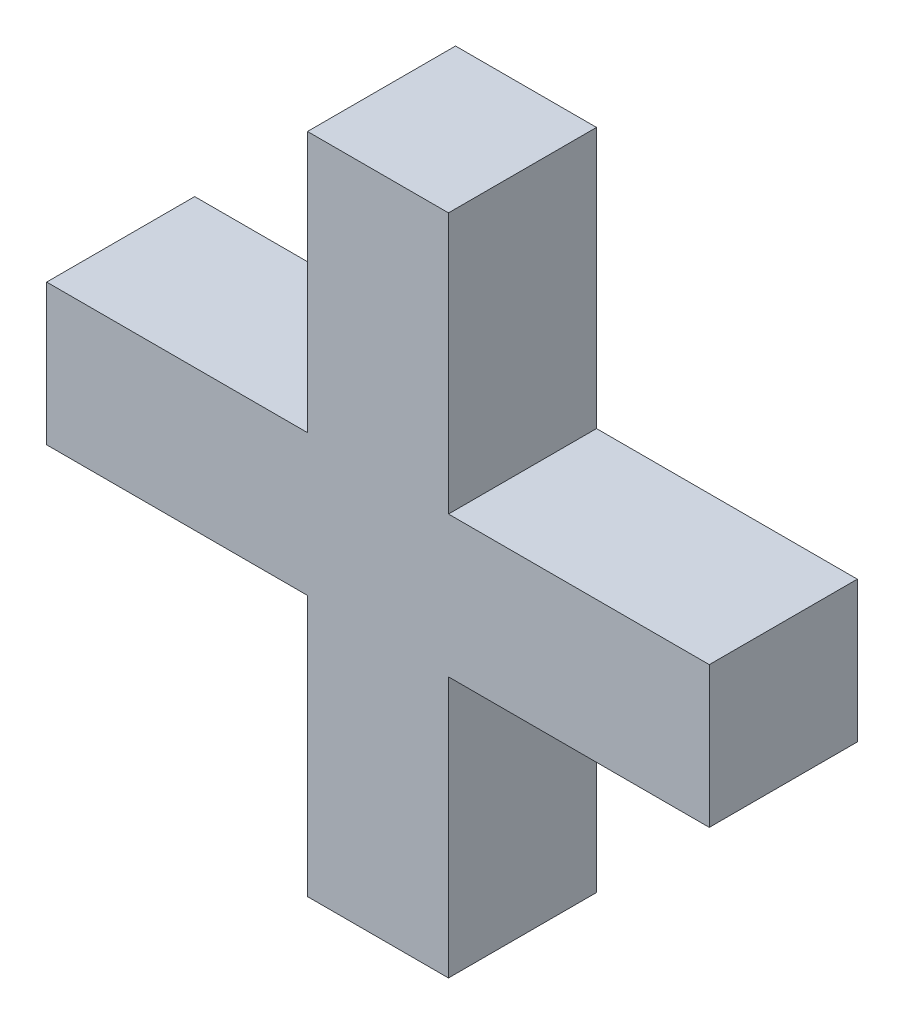
SolidWorks part; units mm, degrees
ref_plane "Спереди" through (0, 0, 0) normal (0, 0, 1) x (1, 0, 0)
ref_plane "Сверху" through (0, 0, 0) normal (0, 1, 0) x (1, 0, 0)
ref_plane "Справа" through (0, 0, 0) normal (1, 0, 0) x (0, 0, -1)
sketch "Эскиз1" plane through (0, 0, 0) normal (0, 0, 1) x (1, 0, 0)
  line L0 (0, 28.5) -> (0, 47)
  line L5 (0, 0) -> (10, 0)
  line L6 (0, 0) -> (0, 18.5)
  line L7 (0, 47) -> (10, 47)
  line L8 (10, 0) -> (10, 18.5)
  line L9 (-18.5, 28.5) -> (0, 28.5)
  line L10 (-18.5, 28.5) -> (-18.5, 18.5)
  line L11 (-18.5, 18.5) -> (0, 18.5)
  line L12 (28.5, 28.5) -> (28.5, 18.5)
  line L13 (10, 28.5) -> (28.5, 28.5)
  line L14 (10, 28.5) -> (10, 47)
  line L15 (10, 18.5) -> (28.5, 18.5)
  dimension "B" = 10
  dimension "D" = 47
extrude "Бобышка-Вытянуть1" add sketch "Эскиз1" along normal blind 10.5
